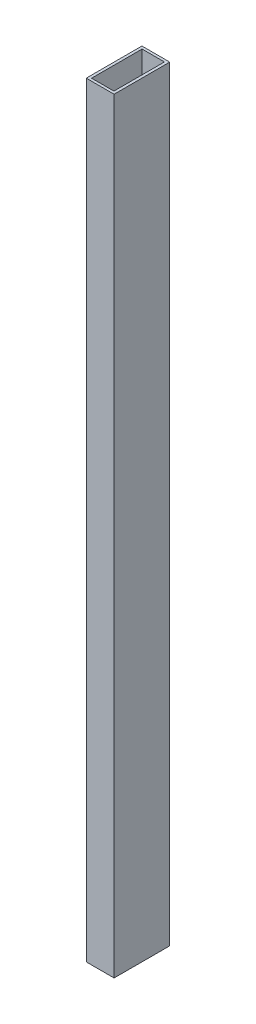
SolidWorks part; units mm, degrees
ref_plane "Front" through (0, 0, 0) normal (0, 0, 1) x (1, 0, 0)
ref_plane "Top" through (0, 0, 0) normal (0, 1, 0) x (1, 0, 0)
ref_plane "Right" through (0, 0, 0) normal (1, 0, 0) x (0, 0, -1)
sketch "Sketch1" plane through (0, 0, 0) normal (0, 1, 0) x (1, 0, 0)
  line L1 (-9.9715, -25.104) -> (15.4285, -25.104)
  line L2 (-9.9715, -25.104) -> (-9.9715, 25.696)
  line L3 (-9.9715, 25.696) -> (15.4285, 25.696)
  line L4 (15.4285, -25.104) -> (15.4285, 25.696)
  line L5 (-9.9715, -25.104) -> (15.4285, 25.696) construction
  line L6 (-9.9715, 25.696) -> (15.4285, -25.104) construction
  point P0 (2.7285, 0.296)
extrude "Boss-Extrude1" add sketch "Sketch1" along normal blind 698.5
sketch "Sketch5" plane through (0, 698.5, 0) normal (0, 1, 0) x (1, 0, 0)
  line L1 (-7.5129, -22.7318) -> (12.9079, -22.7318)
  line L2 (-7.5129, -22.7318) -> (-7.5129, 23.3858)
  line L3 (-7.5129, 23.3858) -> (12.9079, 23.3858)
  line L4 (12.9079, -22.7318) -> (12.9079, 23.3858)
  line L5 (-7.5129, -22.7318) -> (12.9079, 23.3858) construction
  line L6 (-7.5129, 23.3858) -> (12.9079, -22.7318) construction
  point P0 (2.6975, 0.327)
extrude "Cut-Extrude1" cut sketch "Sketch5" against normal blind 508 and the other way blind 10 from offset 0
